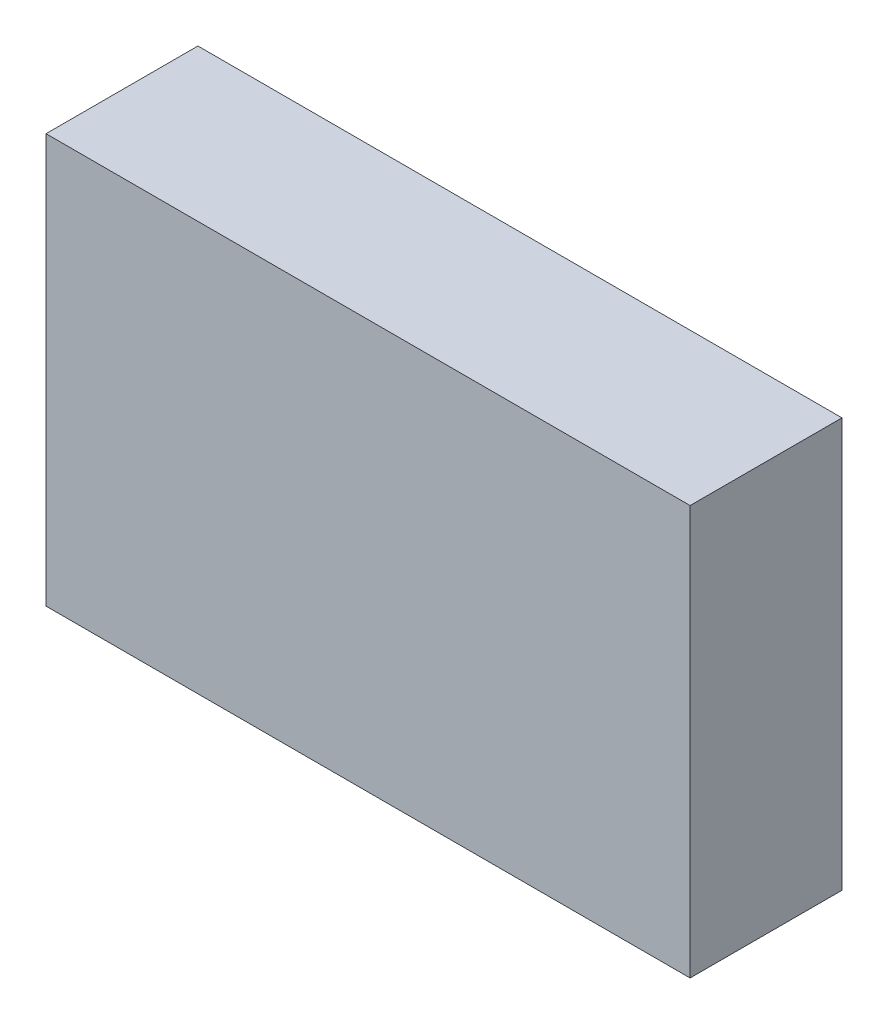
SolidWorks part; units mm, degrees
ref_plane "前视基准面" through (0, 0, 0) normal (0, 0, 1) x (1, 0, 0)
ref_plane "上视基准面" through (0, 0, 0) normal (0, 1, 0) x (1, 0, 0)
ref_plane "右视基准面" through (0, 0, 0) normal (1, 0, 0) x (0, 0, -1)
other "Configuration Table"
sketch "草图1" plane through (0, 0, 0) normal (0, 0, 1) x (1, 0, 0)
  line L1 (-18.9591, 14.2193) -> (23.4494, 14.2193)
  line L2 (-18.9591, 14.2193) -> (-18.9591, -12.7226)
  line L3 (-18.9591, -12.7226) -> (23.4494, -12.7226)
  line L4 (23.4494, 14.2193) -> (23.4494, -12.7226)
extrude "凸台-拉伸1" add sketch "草图1" along normal blind 10 contours L1 L4 L3 L2
